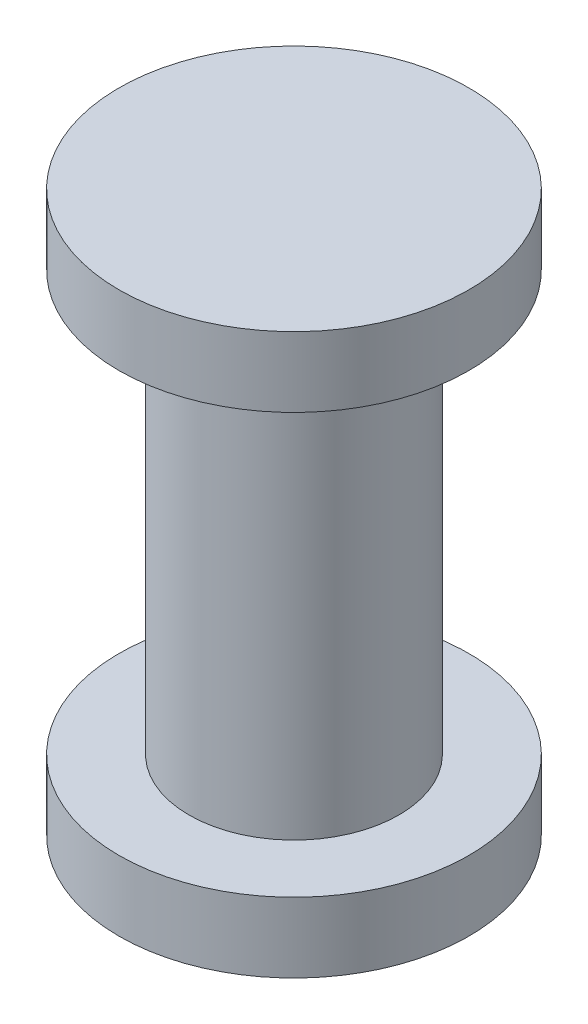
SolidWorks part; units mm, degrees
ref_plane "Front Plane" through (0, 0, 0) normal (0, 0, 1) x (1, 0, 0)
ref_plane "Top Plane" through (0, 0, 0) normal (0, 1, 0) x (1, 0, 0)
ref_plane "Right Plane" through (0, 0, 0) normal (1, 0, 0) x (0, 0, -1)
sketch "Sketch1" plane through (0, 0, 0) normal (0, 0, 1) x (1, 0, 0)
  line L0 (-14.7615, 27.9486) -> (-17.2615, 27.9486)
  line L1 (-14.7615, 27.9486) -> (-14.7615, 19.9486)
  line L2 (-14.7615, 19.9486) -> (-17.2615, 19.9486)
  line L3 (-17.2615, 19.9486) -> (-17.2615, 20.9486)
  line L4 (-17.2615, 20.9486) -> (-16.2615, 20.9486)
  line L5 (-16.2615, 20.9486) -> (-16.2615, 26.9486)
  line L6 (-16.2615, 26.9486) -> (-17.2615, 26.9486)
  line L7 (-17.2615, 26.9486) -> (-17.2615, 27.9486)
  line L8 (-14.7615, 27.9486) -> (-14.7615, 19.9486) construction
  dimension "D1" = 2.5
  dimension "D2" = 2.5
  dimension "D3" = 8
  dimension "D4" = 1.5
  dimension "D5" = 1
  dimension "D6" = 1
revolve "Revolve1" add sketch "Sketch1" angle 360 about L8
